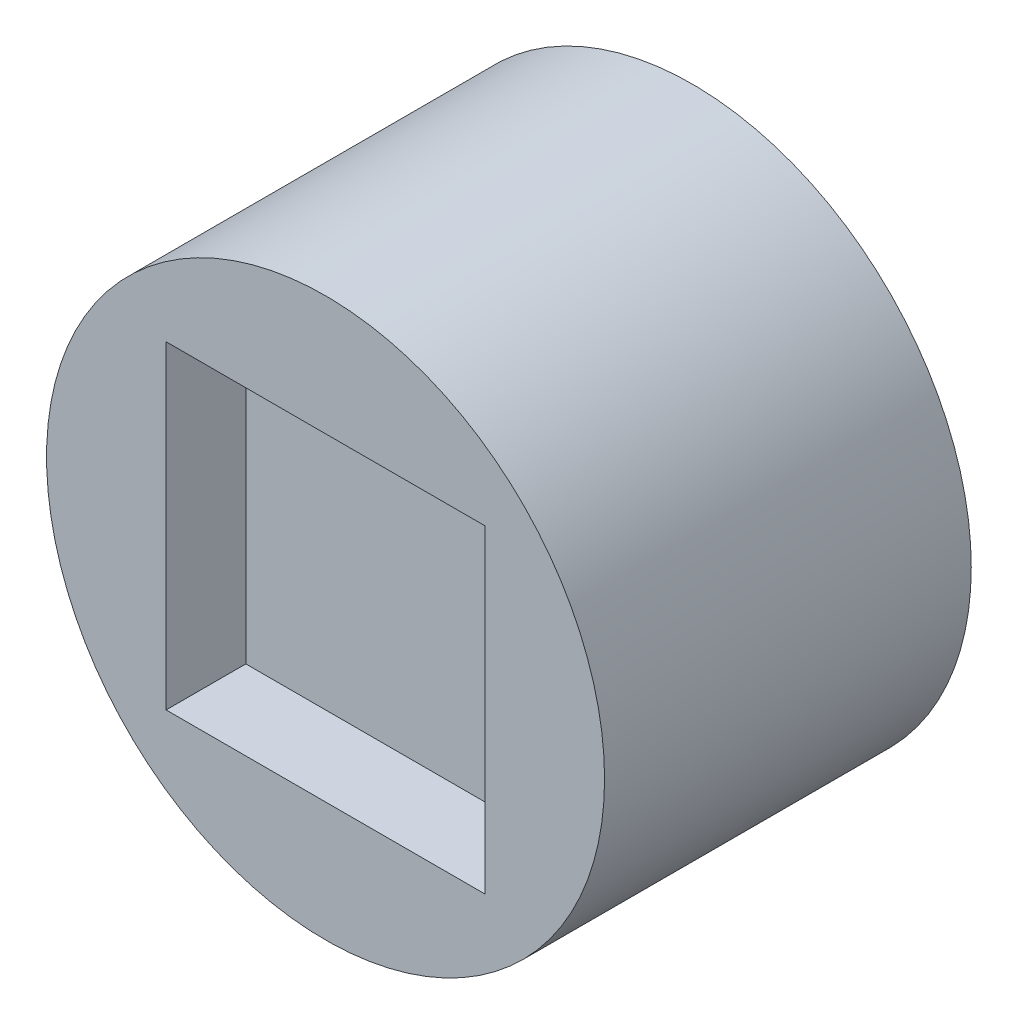
SolidWorks part; units mm, degrees
material "ABS"
ref_plane "Front Plane" through (0, 0, 0) normal (0, 0, 1) x (1, 0, 0)
ref_plane "Top Plane" through (0, 0, 0) normal (0, 1, 0) x (1, 0, 0)
ref_plane "Right Plane" through (0, 0, 0) normal (1, 0, 0) x (0, 0, -1)
sketch "Sketch1" plane through (0, 0, 0) normal (0, 0, 1) x (1, 0, 0)
  circle A0 centre (0, 0) radius 0.175
  dimension "D1" = 0.35
extrude "Boss-Extrude1" add sketch "Sketch1" along normal blind 0.23
sketch "Sketch2" plane through (0, 0, 0.23) normal (0, 0, 1) x (1, 0, 0)
  line L1 (-0.1, 0.1) -> (0.1, 0.1)
  line L2 (-0.1, 0.1) -> (-0.1, -0.1)
  line L3 (-0.1, -0.1) -> (0.1, -0.1)
  line L4 (0.1, 0.1) -> (0.1, -0.1)
  point P4 (0, 0.1)
  point P6 (0.1, 0)
  dimension "D1" = 0.2
  dimension "D2" = 0.2
extrude "Cut-Extrude1" cut sketch "Sketch2" against normal blind 0.05
sketch "Sketch3" plane through (0, 0, 0) normal (0, 0, -1) x (-1, 0, 0)
  line L1 (-0.1, 0.1) -> (0.1, 0.1)
  line L2 (-0.1, 0.1) -> (-0.1, -0.1)
  line L3 (-0.1, -0.1) -> (0.1, -0.1)
  line L4 (0.1, 0.1) -> (0.1, -0.1)
  point P4 (0, 0.1)
  point P6 (-0.1, 0)
  dimension "D1" = 0.2
  dimension "D2" = 0.2
extrude "Cut-Extrude2" cut sketch "Sketch3" against normal blind 0.1
